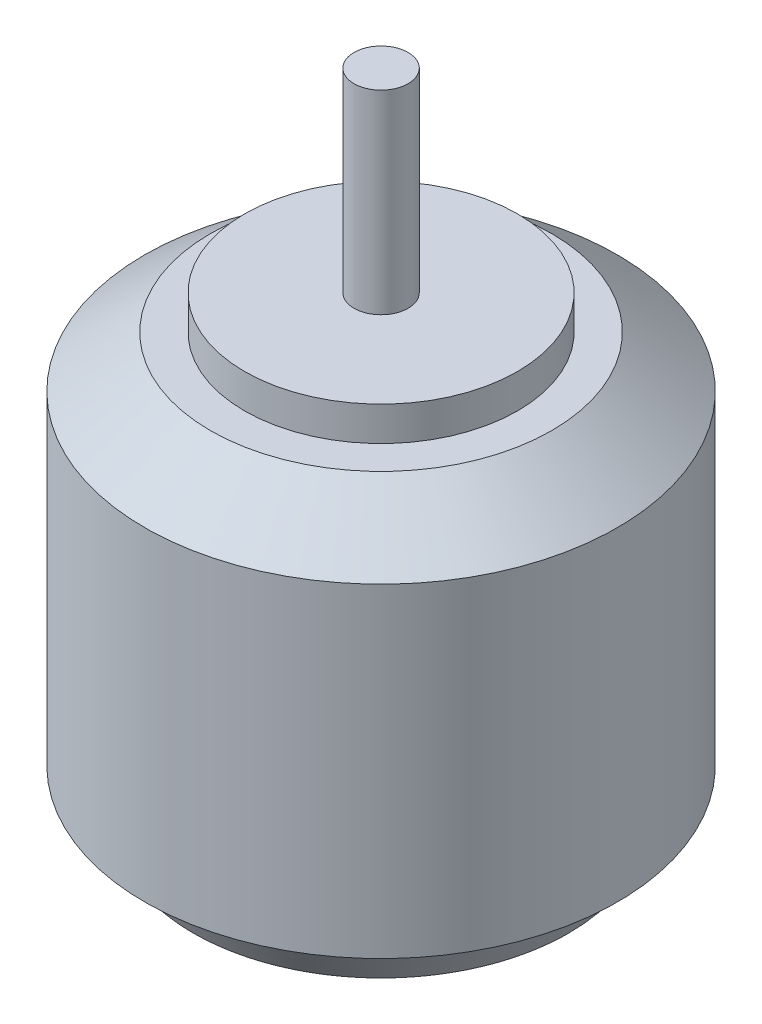
SolidWorks part; units mm, degrees
ref_plane "Front Plane" through (0, 0, 0) normal (0, 0, 1) x (1, 0, 0)
ref_plane "Top Plane" through (0, 0, 0) normal (0, 1, 0) x (1, 0, 0)
ref_plane "Right Plane" through (0, 0, 0) normal (1, 0, 0) x (0, 0, -1)
sketch "Sketch2" plane through (0, 0, 0) normal (0, 0, 1) x (1, 0, 0)
  line L0 (0, 0) -> (11, 0)
  line L2 (13.85, 3) -> (13.85, 22)
  line L3 (13.85, 22) -> (10, 25)
  line L4 (10, 25) -> (8, 25)
  line L5 (8, 25) -> (8, 27)
  line L6 (8, 27) -> (1.585, 27)
  line L7 (1.585, 27) -> (1.585, 38.4)
  line L8 (1.585, 38.4) -> (0, 38.4)
  line L9 (0, 38.4) -> (0, 0)
  line L10 (11, 0) -> (12.7321, 3)
  line L11 (12.7321, 3) -> (13.85, 3)
  dimension "D1" = 1.585
  dimension "D2" = 2
  dimension "D3" = 13.4
  dimension "D4" = 25
  dimension "D5" = 13.85
  dimension "D6" = 11
  dimension "D7" = 120
  dimension "D8" = 3
  dimension "D9" = 3
  dimension "D10" = 10
  dimension "D11" = 2
revolve "Revolve1" add sketch "Sketch2" angle 360 about L9
sketch "Sketch3" plane through (0, 0, 0) normal (0, -1, 0) x (1, 0, 0)
  circle A0 centre (0, 0) radius 9.5 construction
  circle A1 centre (0, 0) radius 8 construction
  circle A4 centre (9.5, 0) radius 1.5
  circle A5 centre (-8, 0) radius 1.5
  circle A6 centre (0, 9.5) radius 1.5
  circle A7 centre (0, -9.5) radius 1.5
  dimension "D1" = 16
  dimension "D2" = 19
  dimension "D3" = 3
extrude "Cut-Extrude1" cut sketch "Sketch3" against normal blind 10
